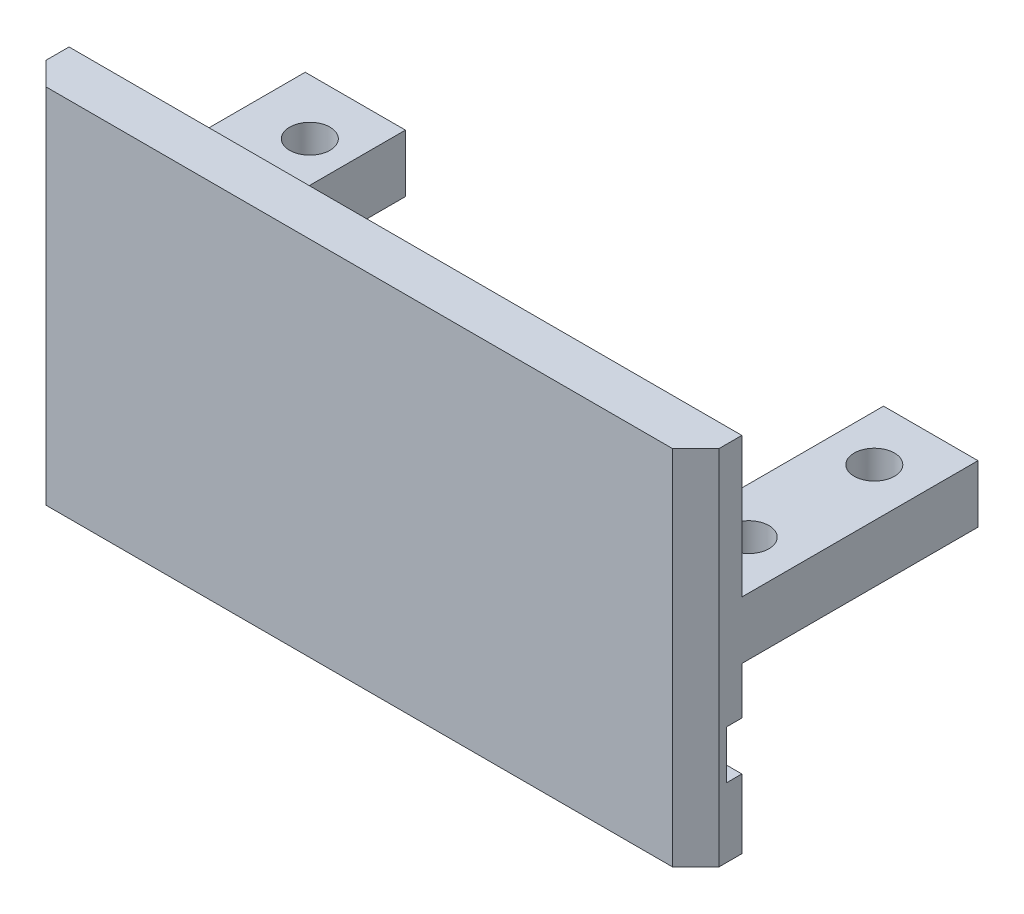
SolidWorks part; units mm, degrees
material "ABS"
ref_plane "Płaszczyzna przednia" through (0, 0, 0) normal (0, 0, 1) x (1, 0, 0)
ref_plane "Płaszczyzna górna" through (0, 0, 0) normal (0, 1, 0) x (1, 0, 0)
ref_plane "Płaszczyzna prawa" through (0, 0, 0) normal (1, 0, 0) x (0, 0, -1)
sketch "Szkic1" plane through (0, 0, 0) normal (0, 0, 1) x (1, 0, 0)
  line L1 (-29.2, 15.725) -> (29.2, 15.725)
  line L2 (-29.2, 15.725) -> (-29.2, -15.725)
  line L3 (-29.2, -15.725) -> (29.2, -15.725)
  line L4 (29.2, 15.725) -> (29.2, -15.725)
  line L5 (-29.2, 15.725) -> (29.2, -15.725) construction
  line L6 (-29.2, -15.725) -> (29.2, 15.725) construction
  point P0 (0, 0)
  dimension "D1" = 58.4
  dimension "D2" = 31.45
extrude "Dodanie-wyciągnięcie1" add sketch "Szkic1" along normal blind 4
sketch "Szkic2" plane through (0, 0, 0) normal (0, 0, -1) x (-1, 0, 0)
  line L0 (-29.2, -15.725) -> (-29.2, 15.725) construction
  line L1 (-29.2, 3.575) -> (-21, 3.575)
  line L2 (-29.2, 3.575) -> (-29.2, -1.425)
  line L3 (-29.2, -1.425) -> (-21, -1.425)
  line L4 (-21, 3.575) -> (-21, -1.425)
  line L5 (29.2, 15.725) -> (29.2, -15.725) construction
  line L6 (20.5, 3.575) -> (29.2, 3.575)
  line L7 (20.5, 3.575) -> (20.5, -1.425)
  line L8 (20.5, -1.425) -> (29.2, -1.425)
  line L9 (29.2, 3.575) -> (29.2, -1.425)
  line L12 (29.2, -15.725) -> (-29.2, -15.725) construction
  line L13 (-10.5, 21.6947) -> (-10.5, -27.4208) construction
  dimension "D1" = 18.7
  dimension "D2" = 10.5
  dimension "D3" = 19.3
  dimension "D4" = 5
  dimension "D5" = 31
  dimension "D6" = 8.2
  dimension "D7" = 8.7
extrude "Dodanie-wyciągnięcie2" add sketch "Szkic2" along normal blind 20.5
sketch "Szkic3" plane through (0, 3.575, 0) normal (0, 1, 0) x (1, 0, 0)
  line L0 (-29.2, 10.25) -> (29.2, 10.25) construction
  line L3 (-29.2, 20.5) -> (-29.2, 0) construction
  line L4 (29.2, 20.5) -> (29.2, 0) construction
  line L5 (-24, 4.8) -> (25, 4.8) construction
  line L6 (-29.2, 0) -> (-20.5, 0) construction
  line L8 (-20.5, 20.5) -> (-20.5, 0) construction
  line L9 (21, 20.5) -> (21, 0) construction
  circle A0 centre (25, 4.8) radius 1.75
  circle A1 centre (-24, 4.8) radius 1.75
  circle A2 centre (25, 15.7) radius 1.75
  circle A3 centre (-24, 15.7) radius 1.75
  dimension "D1" = 3.5
  dimension "D2" = 3.5
  dimension "D4" = 3.5
  dimension "D5" = 4
  dimension "D3" = 4.8
extrude "Wytnij-wyciągnięcie1" cut sketch "Szkic3" against normal up to next
sketch "Szkic5" plane through (0, 0, 0) normal (0, 0, -1) x (-1, 0, 0)
  line L0 (-29.2, -15.725) -> (-29.2, -1.425) construction
  line L1 (29.2, -1.425) -> (29.2, -15.725) construction
  line L2 (-29.2, -5.525) -> (29.2, -5.525)
  line L3 (-29.2, -5.525) -> (-29.2, -9.725)
  line L4 (-29.2, -9.725) -> (29.2, -9.725)
  line L5 (29.2, -5.525) -> (29.2, -9.725)
  line L6 (29.2, -15.725) -> (-29.2, -15.725) construction
  dimension "D1" = 4.2
  dimension "D2" = 6
extrude "Wytnij-wyciągnięcie2" cut sketch "Szkic5" against normal blind 1.35
chamfer "Sfazowanie1" distance 2 angle 45 2 edges at (29.2, 0, 4) (-29.2, 0, 4)
